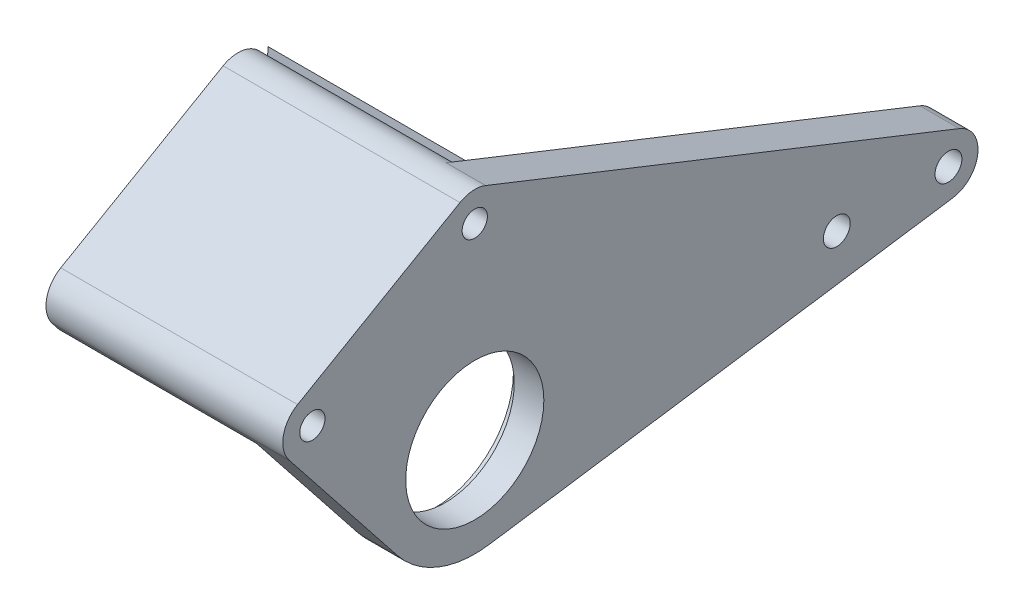
SolidWorks part; units mm, degrees
ref_plane "Front Plane" through (0, 0, 0) normal (0, 0, 1) x (1, 0, 0)
ref_plane "Top Plane" through (0, 0, 0) normal (0, 1, 0) x (1, 0, 0)
ref_plane "Right Plane" through (0, 0, 0) normal (1, 0, 0) x (0, 0, -1)
sketch "Sketch1" plane through (0, 0, 0) normal (1, 0, 0) x (0, 0, -1)
  line L0 (1.7528, 4.4282) -> (-74.4472, 34.5907)
  line L1 (-78.5812, 34.2869) -> (-104.7027, 19.2057)
  line L2 (-106.0548, 12.1242) -> (-88.6443, -9.8568)
  line L3 (-73.8849, -15.7053) -> (0.6945, -4.7116)
  line L4 (-102.3215, 15.0813) -> (-76.2, 0) construction
  line L5 (-76.2, 0) -> (-76.2, 30.1625) construction
  line L6 (0, 0) -> (-76.2, 0) construction
  circle A0 centre (0, 0) radius 2.159
  arc A1 (0.6945, -4.7116) -> (1.7528, 4.4282) centre (0, 0) ccw
  arc A2 (-74.4472, 34.5907) -> (-78.5812, 34.2869) centre (-76.2, 30.1625) ccw
  arc A3 (-104.7027, 19.2057) -> (-106.0548, 12.1242) centre (-102.3215, 15.0813) ccw
  arc A4 (-88.6443, -9.8568) -> (-73.8849, -15.7053) centre (-76.2, 0) ccw
  circle A5 centre (-76.2, 0) radius 11.1125
  circle A6 centre (-76.2, 30.1625) radius 2.032
  circle A7 centre (-76.2, 0) radius 26.1938 construction
  circle A8 centre (-102.3215, 15.0813) radius 2.032
  circle A9 centre (-17.9605, 0) radius 2.159
  dimension "D1" = 4.318
  dimension "D2" = 9.525
  dimension "D3" = 22.225
  dimension "D4" = 4.7625
  dimension "D5" = 15.875
  dimension "D6" = 52.3875
  dimension "D10" = 4.064
  dimension "D7" = 30.1625
  dimension "D8" = 76.2
  dimension "D9" = 60
  dimension "D11" = 17.9605
extrude "Boss-Extrude1" add sketch "Sketch1" along normal blind 6.35
sketch "Sketch2" plane through (6.35, 0, 0) normal (1, 0, 0) x (0, 0, -1)
  circle A0 centre (-76.2, 0) radius 12.573
  dimension "D1" = 25.146
extrude "Cut-Extrude1" cut sketch "Sketch2" against normal blind 1.5875
sketch "Sketch3" plane through (6.35, 0, 0) normal (1, 0, 0) x (0, 0, -1)
  line L1 (-76.2, 33.902) -> (-79.4385, 32.0322)
  line L2 (-79.4385, 32.0322) -> (-79.4385, 28.2928)
  line L3 (-79.4385, 28.2928) -> (-76.2, 26.423)
  line L4 (-76.2, 26.423) -> (-72.9615, 28.2928)
  line L5 (-72.9615, 28.2928) -> (-72.9615, 32.0322)
  line L6 (-72.9615, 32.0322) -> (-76.2, 33.902)
  line L7 (-102.3215, 18.8207) -> (-105.56, 16.951)
  line L8 (-105.56, 16.951) -> (-105.56, 13.2115)
  line L9 (-105.56, 13.2115) -> (-102.3215, 11.3418)
  line L10 (-102.3215, 11.3418) -> (-99.083, 13.2115)
  line L11 (-99.083, 13.2115) -> (-99.083, 16.951)
  line L12 (-99.083, 16.951) -> (-102.3215, 18.8207)
  line L13 (-78.5813, 34.2869) -> (-104.7027, 19.2057)
  line L14 (-106.0548, 12.1242) -> (-101.5807, 6.4756)
  line L16 (-71.4639, 30.6634) -> (-71.374, 33.3742)
  line L17 (1.7528, 4.4282) -> (-74.4472, 34.5907) construction
  line L18 (-71.374, 25.7453) -> (-71.374, 33.3742)
  line L20 (-78.5812, 34.2869) -> (-104.7027, 19.2057) construction
  line L21 (-106.0548, 12.1242) -> (-88.6443, -9.8568) construction
  circle A0 centre (-76.2, 30.1625) radius 3.2385 construction
  circle A1 centre (-102.3215, 15.0813) radius 3.2385 construction
  arc A4 (-71.4639, 30.6634) -> (-78.5813, 34.2869) centre (-76.2, 30.1625) ccw
  arc A5 (-104.7027, 19.2057) -> (-106.0548, 12.1242) centre (-102.3215, 15.0813) ccw
  arc A6 (-101.5807, 6.4756) -> (-71.374, 25.7453) centre (-76.2, 0) cw
  arc A7 (-74.4472, 34.5907) -> (-78.5812, 34.2869) centre (-76.2, 30.1625) ccw construction
  arc A8 (-104.7027, 19.2057) -> (-106.0548, 12.1242) centre (-102.3215, 15.0813) ccw construction
  dimension "D4" = 26.1937
  dimension "D1" = 6.477
  dimension "D2" = 6.477
  dimension "D3" = 1.5875
extrude "Boss-Extrude2" add sketch "Sketch3" along normal blind 31.75
fillet "Fillet1" radius 3.175 2 edges at (22.225, 25.7453, 71.374) (22.225, 6.4756, 101.5807)
mirror "Mirror1" about plane through (6.35, 0, 0) normal (1, 0, 0) of bodies 104 102
delete or keep bodies "Body-Delete/Keep 1" type delete bodies bodies 104
